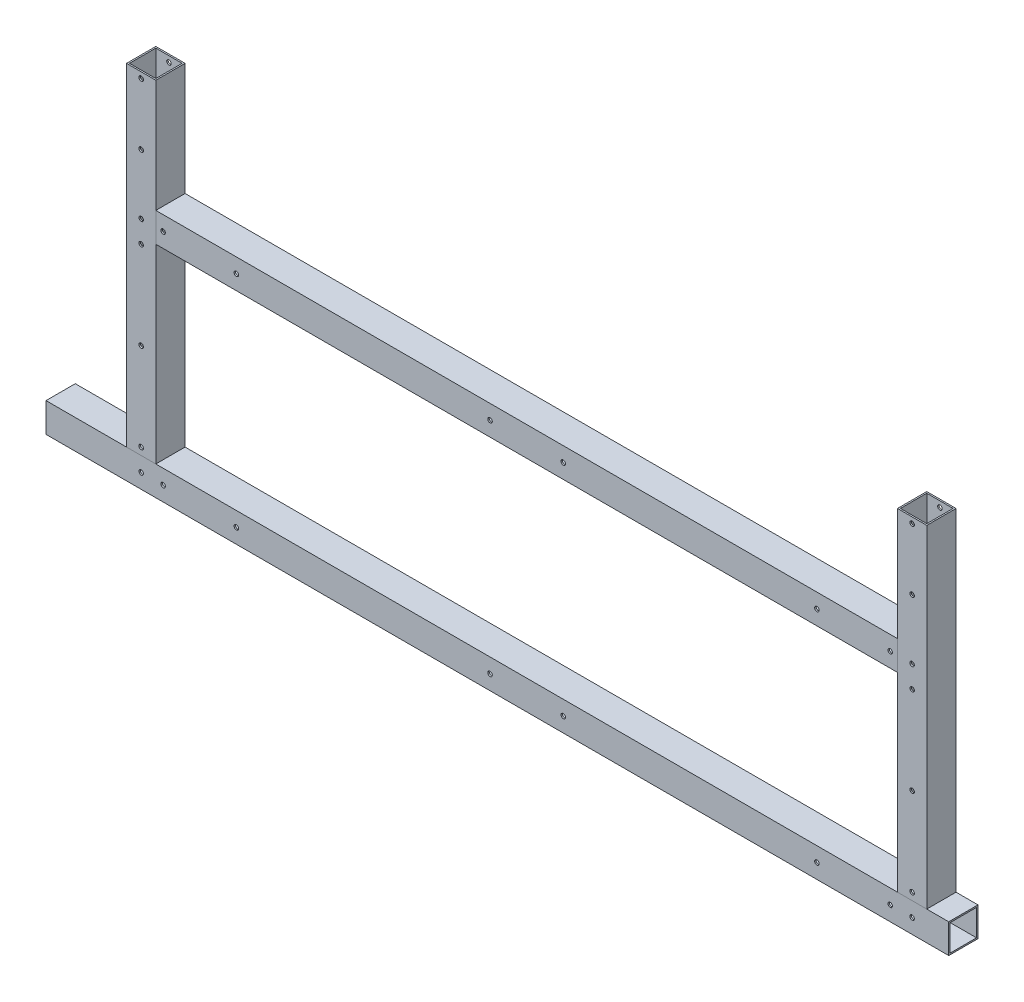
SolidWorks part; units mm, degrees
material "6061 合金"
ref_plane "前视基准面" through (0, 0, 0) normal (0, 0, 1) x (1, 0, 0)
ref_plane "上视基准面" through (0, 0, 0) normal (0, 1, 0) x (1, 0, 0)
ref_plane "右视基准面" through (0, 0, 0) normal (1, 0, 0) x (0, 0, -1)
sketch3d "3D草图1"
  line L0 (-65, 0, 0) -> (551.6, 0, 0)
  line L1 (526.6, 0, 0) -> (526.6, 237, 0)
  line L2 (0, 0, 0) -> (0, 237, 0)
  line L3 (0, 150, 0) -> (526.6, 150, 0)
  line L4 (526.6, 237, 0) -> (0, 237, 0) construction
  dimension "D1" = 526.6
  dimension "D2" = 150
  dimension "D3" = 237
  dimension "D5" = 25
  dimension "D6" = 65
other "方形管 20X20X1(1)"
ref_plane "基准面1" through (0, 0, 0) normal (0, 1, 0) x (1, 0, 0)
sketch "草图1" plane through (0, 0, 0) normal (0, 1, 0) x (1, 0, 0)
  line L0 (-9, 9) -> (9, 9)
  line L1 (-10, 10) -> (10, 10)
  line L2 (-10, 10) -> (-10, -10)
  line L3 (-10, -10) -> (10, -10)
  line L4 (10, 10) -> (10, -10)
  line L5 (-10, 10) -> (10, -10) construction
  line L6 (-10, -10) -> (10, 10) construction
  line L7 (9, 9) -> (9, -9)
  line L8 (-9, -9) -> (9, -9)
  line L9 (-9, 9) -> (-9, -9)
  point P0 (0, 0)
  point P10 (0, 0)
  dimension "D1" = 20
  dimension "D2" = 1
sketch "草图3" plane through (0, 0, -10) normal (0, 0, -1) x (-1, 0, 0)
  circle A0 centre (-526.6, 233) radius 1.55 construction
  circle A1 centre (-526.6, 233) radius 1.55
  circle A2 centre (-461.6, 150) radius 1.55 construction
  circle A3 centre (-511.6, 150) radius 1.55 construction
  circle A4 centre (-526.6, 135) radius 1.55 construction
  circle A5 centre (-526.6, 150) radius 1.55 construction
  circle A6 centre (-526.6, 191) radius 1.55 construction
  circle A7 centre (-461.6, 150) radius 1.55
  circle A8 centre (-511.6, 150) radius 1.55
  circle A9 centre (-526.6, 135) radius 1.55
  circle A10 centre (-526.6, 150) radius 1.55
  circle A11 centre (-526.6, 191) radius 1.55
  circle A12 centre (-461.6, 0) radius 1.55 construction
  circle A13 centre (-511.6, 0) radius 1.55 construction
  circle A14 centre (-526.6, 0) radius 1.55 construction
  circle A15 centre (-526.6, 15) radius 1.55 construction
  circle A16 centre (-526.6, 75) radius 1.55 construction
  circle A17 centre (-461.6, 0) radius 1.55
  circle A18 centre (-511.6, 0) radius 1.55
  circle A19 centre (-526.6, 0) radius 1.55
  circle A20 centre (-526.6, 15) radius 1.55
  circle A21 centre (-526.6, 75) radius 1.55
  circle A22 centre (-238.3, 150) radius 1.55 construction
  circle A23 centre (-288.3, 150) radius 1.55 construction
  circle A24 centre (-238.3, 150) radius 1.55
  circle A25 centre (-288.3, 150) radius 1.55
  circle A26 centre (0, 75) radius 1.55 construction
  circle A27 centre (0, 135) radius 1.55 construction
  circle A28 centre (0, 150) radius 1.55 construction
  circle A29 centre (-15, 150) radius 1.55 construction
  circle A30 centre (-65, 150) radius 1.55 construction
  circle A31 centre (0, 75) radius 1.55
  circle A32 centre (0, 135) radius 1.55
  circle A33 centre (0, 150) radius 1.55
  circle A34 centre (-15, 150) radius 1.55
  circle A35 centre (-65, 150) radius 1.55
  circle A36 centre (-65, 0) radius 1.55 construction
  circle A37 centre (-15, 0) radius 1.55 construction
  circle A38 centre (0, 0) radius 1.55 construction
  circle A39 centre (0, 15) radius 1.55 construction
  circle A40 centre (-65, 0) radius 1.55
  circle A41 centre (-15, 0) radius 1.55
  circle A42 centre (0, 0) radius 1.55
  circle A43 centre (0, 15) radius 1.55
  circle A44 centre (-288.3, 0) radius 1.55 construction
  circle A45 centre (-238.3, 0) radius 1.55 construction
  circle A46 centre (-288.3, 0) radius 1.55
  circle A47 centre (-238.3, 0) radius 1.55
  circle A48 centre (0, 191) radius 1.55 construction
  circle A49 centre (0, 233) radius 1.55 construction
  circle A50 centre (0, 191) radius 1.55
  circle A51 centre (0, 233) radius 1.55
extrude "切除-拉伸1" cut sketch "草图3" against normal through all
